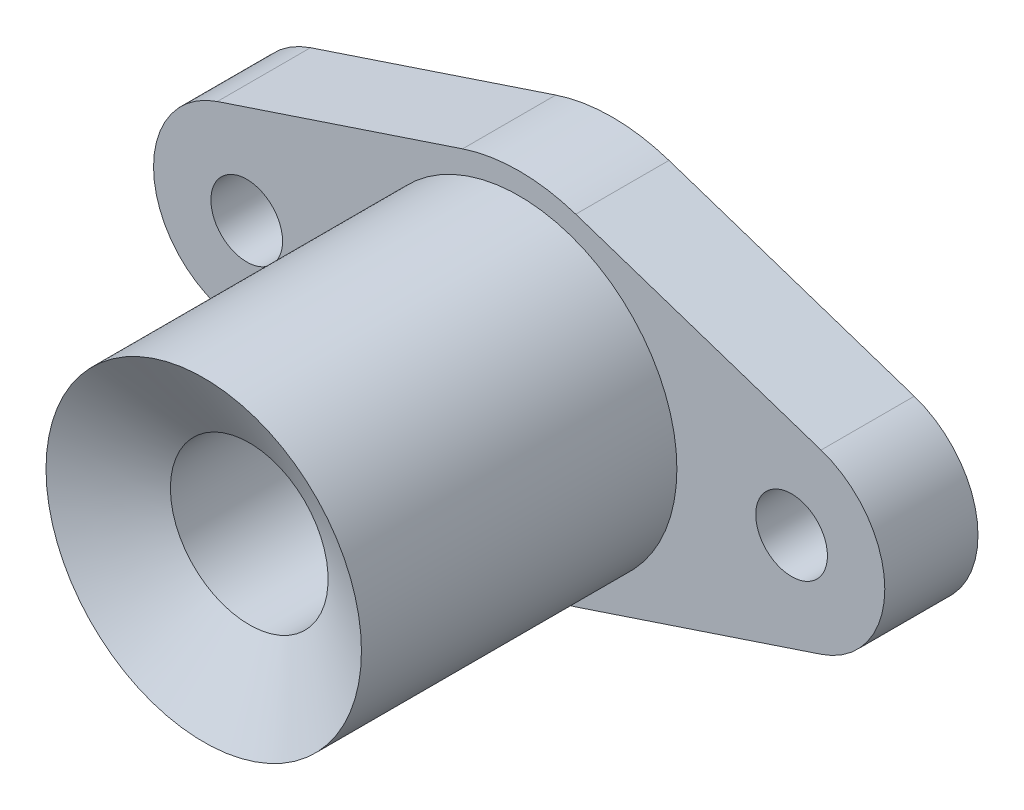
SolidWorks part; units mm, degrees
ref_plane "Piano frontale" through (0, 0, 0) normal (0, 0, 1) x (1, 0, 0)
ref_plane "Piano superiore" through (0, 0, 0) normal (0, 1, 0) x (1, 0, 0)
ref_plane "Piano destro" through (0, 0, 0) normal (1, 0, 0) x (0, 0, -1)
sketch "Schizzo2" plane through (0, 0, 0) normal (0, 0, 1) x (1, 0, 0)
  line L2 (-42.1053, 12.3348) -> (-7.8947, 23.7207)
  line L3 (42.1053, 12.3348) -> (7.8947, 23.7207)
  line L4 (42.1053, -12.3348) -> (7.8947, -23.7207)
  line L5 (-42.1053, -12.3348) -> (-7.8947, -23.7207)
  arc A0 (-7.8947, -23.7207) -> (7.8947, -23.7207) centre (0, 0) ccw
  arc A1 (-42.1053, 12.3348) -> (-42.1053, -12.3348) centre (-38, 0) ccw
  arc A2 (42.1053, 12.3348) -> (42.1053, -12.3348) centre (38, 0) cw
  arc A3 (7.8947, 23.7207) -> (-7.8947, 23.7207) centre (0, 0) ccw
  circle A4 centre (38, 0) radius 5
  circle A5 centre (-38, 0) radius 5
  dimension "D1" = 26
  dimension "D2" = 50
  dimension "D3" = 10
extrude "Estrusione-Estrusione1" add sketch "Schizzo2" against normal blind 13
sketch "Schizzo3" plane through (0, 0, 0) normal (0, 0, 1) x (1, 0, 0)
  circle A0 centre (0, 0) radius 22
  dimension "D1" = 44
extrude "Estrusione-Estrusione2" add sketch "Schizzo3" along normal blind 44
sketch "Schizzo5" plane through (0, 0, 0) normal (0, 1, 0) x (1, 0, 0)
  line L0 (0, 13) -> (0, -44) construction
  line L1 (7.8947, 13) -> (-7.8947, 13) construction
  line L2 (-22, -44) -> (22, -44) construction
  line L3 (0, 13) -> (-11, 13)
  line L4 (-7.8947, 13) -> (-42.1053, 13) construction
  line L5 (-11, 13) -> (-11, -37.6491)
  line L6 (-11, -37.6491) -> (-22, -44)
  line L7 (-22, -44) -> (0, -44)
  line L8 (0, 13) -> (0, -44)
  point P9 (0, 0)
  point P13 (0, 0)
  point P14 (0, 0)
  dimension "D1" = 30
  dimension "D2" = 22
revolve "Taglia-Rivoluzione2" cut sketch "Schizzo5" angle 360 about L0
